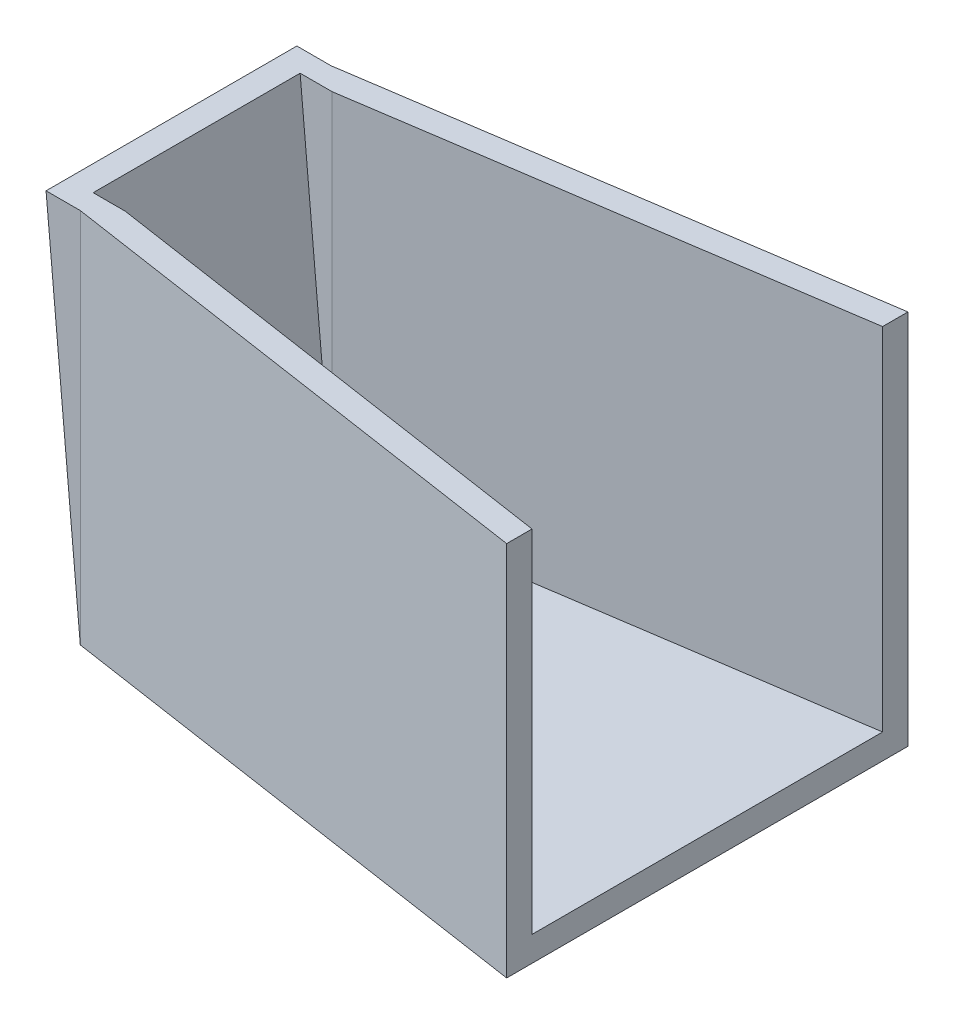
SolidWorks part; units mm, degrees
ref_plane "Front Plane" through (0, 0, 0) normal (0, 0, 1) x (1, 0, 0)
ref_plane "Top Plane" through (0, 0, 0) normal (0, 1, 0) x (1, 0, 0)
ref_plane "Right Plane" through (0, 0, 0) normal (1, 0, 0) x (0, 0, -1)
sketch "Sketch1" plane through (0, 0, 0) normal (0, 1, 0) x (1, 0, 0)
  line L0 (0, -24) -> (0, 24)
  line L1 (0, 0) -> (-60, 0)
  line L2 (-60, -15) -> (-60, 15)
  line L3 (-60, 15) -> (0, 24)
  line L4 (-60, -15) -> (0, -24)
  point P4 (0, 0)
  point P10 (-60, 0)
  dimension "D1" = 60
  dimension "D2" = 30
  dimension "D3" = 48
extrude "Boss-Extrude1" add sketch "Sketch1" along normal blind 3 contours L3 L2 L1 L0 | L2 L4 L0 L1
sketch "Sketch3" plane through (0, 0, 0) normal (0, 0, 1) x (1, 0, 0)
  line L0 (-60, 3) -> (-60, 0) construction
  line L1 (-60, 3) -> (-60, 0) construction
  line L2 (-60, 0) -> (-64.0953, 45)
  line L3 (-64.0953, 45) -> (-60, 45) construction
  line L4 (-60, 45) -> (-60, 0) construction
  line L5 (-61.0829, 45) -> (-56.9876, 0)
  line L6 (-60, 0) -> (0, 0) construction
  line L7 (-60, 0) -> (-56.9876, 0)
  line L8 (-56.9876, 0) -> (-60, 0)
  line L9 (-64.0953, 45) -> (-61.0829, 45)
  dimension "D1" = 45
  dimension "D2" = 5.2
  dimension "D3" = 3
extrude "Boss-Extrude2" add sketch "Sketch3" along normal mid plane 30 contours L9 L2 L7 L5
sketch "Sketch4" plane through (0, 3, 0) normal (0, 1, 0) x (1, 0, 0)
  line L0 (0, 20.9664) -> (-57.2606, 12.3773)
  line L1 (-54.2606, 12.8273) -> (-54.2606, 12.8273)
  line L3 (-54.2606, -12.8273) -> (-54.2606, -12.8273)
  line L4 (-57.2606, -12.3773) -> (0, -20.9664)
  line L6 (-57.2606, -15) -> (-60, -15)
  line L7 (-60, -15) -> (0, -24)
  line L8 (0, -24) -> (0, 24)
  line L9 (0, 24) -> (-60, 15)
  line L10 (-60, 15) -> (-57.2606, 15)
  line L11 (-57.2606, 15) -> (-57.2606, -15)
  line L12 (-57.2606, -15) -> (-60, -15)
  line L13 (-60, -15) -> (0, -24)
  line L14 (0, -24) -> (0, 24)
  line L15 (0, 24) -> (-60, 15)
  line L16 (-60, 15) -> (-57.2606, 15)
  line L17 (-57.2606, 15) -> (-57.2606, -15)
  line L18 (-3, -20.5164) -> (-3, 20.5164) construction
  line L19 (-3, 20.5164) -> (-54.2606, 12.8273) construction
  line L20 (-54.2606, -12.8273) -> (-3, -20.5164) construction
  line L21 (-54.2606, 12.8273) -> (-54.2606, -12.8273) construction
  line M7 (-57.2606, -15) -> (-60, -15)
  line M8 (-60, -15) -> (0, -24)
  line M9 (0, -24) -> (0, 24)
  line M10 (0, 24) -> (-60, 15)
  line M11 (-60, 15) -> (-57.2606, 15)
  line M12 (-57.2606, 15) -> (-57.2606, -15)
  dimension "D1" = 0
  dimension "D2" = 3
extrude "Boss-Extrude3" add sketch "Sketch4" along normal blind 42 contours L0 M9 M10 M11 M12 | L4 M12 M7 M8 M9
sketch "Sketch6" plane through (-57.2606, 0, 0) normal (-1, 0, 0) x (0, 0, 1)
  line L0 (-12.3773, 44.7089) -> (-12.3773, 45)
  line L1 (-12.3773, 45) -> (-12.3773, 3) construction
  line L2 (-12.3773, 45) -> (-12.3773, 44.7089)
  line L3 (-12.3773, 45) -> (-12.3773, 0)
  line L4 (-15, 45) -> (-15, 0)
  line L5 (-15, 0) -> (15, 0)
  line L6 (15, 0) -> (15, 45)
  line L7 (15, 45) -> (-15, 45)
  line L8 (-15, 45) -> (-15, 0)
  line L9 (-15, 0) -> (15, 0)
  line L10 (15, 0) -> (15, 45)
  line L11 (15, 45) -> (12.3773, 45)
  line L12 (12.3773, 45) -> (12.3773, 3) construction
  line L13 (12.3773, 45) -> (12.3773, 0)
  line L14 (-12.3773, 45) -> (-15, 45)
  line M5 (-15, 3) -> (-12.3773, 3)
  line M6 (-12.3773, 3) -> (-12.3773, 45)
  line M8 (-15, 45) -> (-15, 3)
  dimension "D1" = 0
extrude "Boss-Extrude4" add sketch "Sketch6" along normal blind 4 contours L14 M6 M8 M5 | L11 L13 L9 L10
sketch "Sketch7" plane through (0, 0, 15) normal (0, 0, 1) x (1, 0, 0)
  line L0 (-61.2606, 13.8519) -> (-60, 0)
  line L1 (-60, 0) -> (-61.2606, 0)
  line L2 (-61.2606, 13.8519) -> (-61.2606, 0)
  line L5 (-64.0953, 45) -> (-61.2606, 13.8519)
  line L6 (-61.2606, 13.8519) -> (-61.2606, 0)
  line L7 (-61.2606, 0) -> (-60, 0)
  line L8 (-60, 0) -> (-60, 45)
  line L9 (-60, 45) -> (-64.0953, 45)
  line L10 (-64.0953, 45) -> (-61.2606, 13.8519)
  line L11 (-61.2606, 13.8519) -> (-61.2606, 0)
  line L12 (-61.2606, 0) -> (-60, 0)
  line L13 (-60, 0) -> (-60, 45) construction
  line L14 (-60, 45) -> (-64.0953, 45)
  line M8 (-61.2606, 13.8519) -> (-61.2606, 0)
  line M9 (-61.2606, 0) -> (-60, 0)
  dimension "D1" = 0
extrude "Cut-Extrude1" cut sketch "Sketch7" against normal through all contours L0 M8 M9
